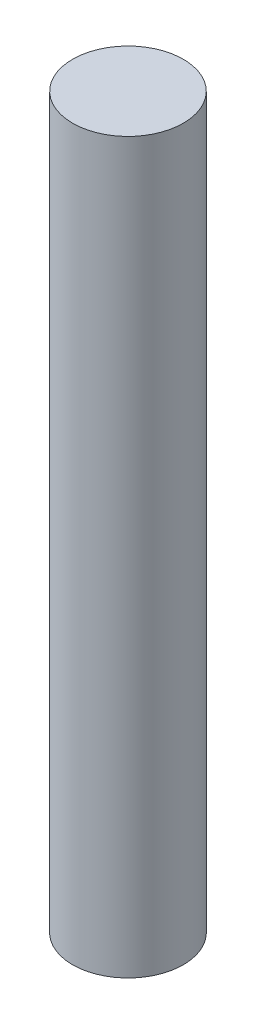
SolidWorks part; units mm, degrees
ref_plane "Front Plane" through (0, 0, 0) normal (0, 0, 1) x (1, 0, 0)
ref_plane "Top Plane" through (0, 0, 0) normal (0, 1, 0) x (1, 0, 0)
ref_plane "Right Plane" through (0, 0, 0) normal (1, 0, 0) x (0, 0, -1)
sketch "Sketch1" plane through (0, 0, 0) normal (0, 1, 0) x (1, 0, 0)
  circle A0 centre (0, 0) radius 4.826
  dimension "D1" = 9.652
extrude "Boss-Extrude1" add sketch "Sketch1" along normal blind 63.5
